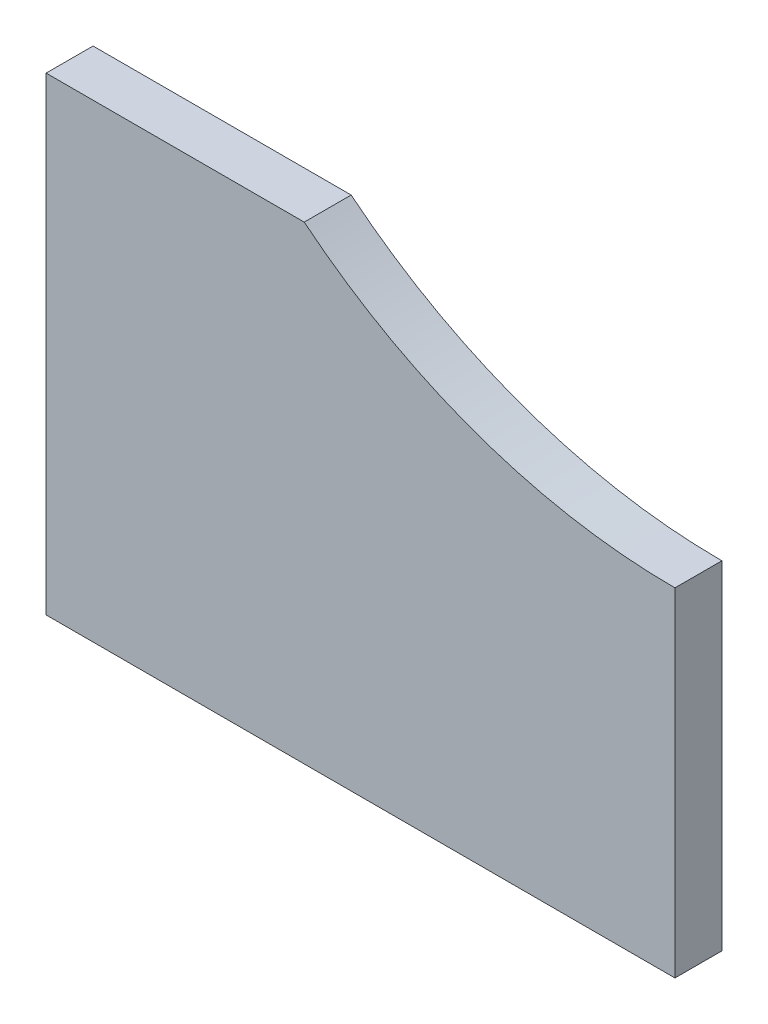
SolidWorks part; units mm, degrees
ref_plane "Front" through (0, 0, 0) normal (0, 0, 1) x (1, 0, 0)
ref_plane "Top" through (0, 0, 0) normal (0, 1, 0) x (1, 0, 0)
ref_plane "Right" through (0, 0, 0) normal (1, 0, 0) x (0, 0, -1)
sketch "Sketch1" plane through (0, 0, 0) normal (0, 0, 1) x (1, 0, 0)
  line L0 (-85.09, 63.5) -> (-85.09, -63.5)
  line L1 (-85.09, -63.5) -> (85.09, -63.5)
  line L2 (85.09, -63.5) -> (85.09, 27.94)
  line L3 (-85.09, 63.5) -> (-15.24, 63.5)
  line L4 (82.7017, 27.94) -> (165.1166, 27.94) construction
  line L5 (50, 0) -> (-50, 0) construction
  line L6 (0, -50) -> (0, 50) construction
  circle A0 centre (85.09, 187.257) radius 159.317 construction
  arc A2 (-15.24, 63.5) -> (85.09, 27.94) centre (85.09, 187.257) ccw
  point P10 (-85.09, 0)
  point P13 (0, -63.5)
  dimension "D1" = 69.85
  dimension "D2" = 127
  dimension "D3" = 170.18
  dimension "D4" = 91.44
extrude "Boss-Extrude2" add sketch "Sketch1" along normal mid plane 12.7
